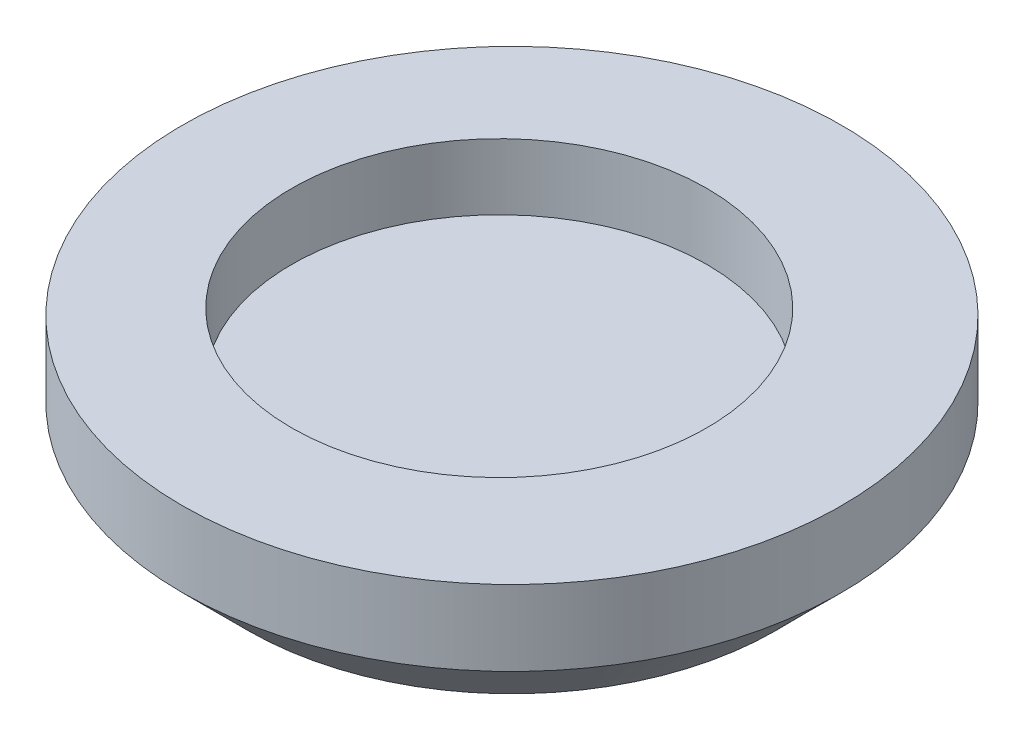
SolidWorks part; units mm, degrees
material "Rubber"
ref_plane "Front Plane" through (0, 0, 0) normal (0, 0, 1) x (1, 0, 0)
ref_plane "Top Plane" through (0, 0, 0) normal (0, 1, 0) x (1, 0, 0)
ref_plane "Right Plane" through (0, 0, 0) normal (1, 0, 0) x (0, 0, -1)
sketch "Sketch1" plane through (0, 0, 0) normal (0, 1, 0) x (1, 0, 0)
  circle A0 centre (1.3457, 0) radius 35
  dimension "D1" = 70
extrude "Boss-Extrude1" add sketch "Sketch1" along normal blind 15
chamfer "Chamfer2" distance 7 angle 45 1 edges at (1.3457, 0, 35)
sketch "Sketch2" plane through (0, 15, 0) normal (0, 1, 0) x (1, 0, 0)
  circle A0 centre (0, 0) radius 22.0419
extrude "Cut-Extrude1" cut sketch "Sketch2" against normal blind 7
